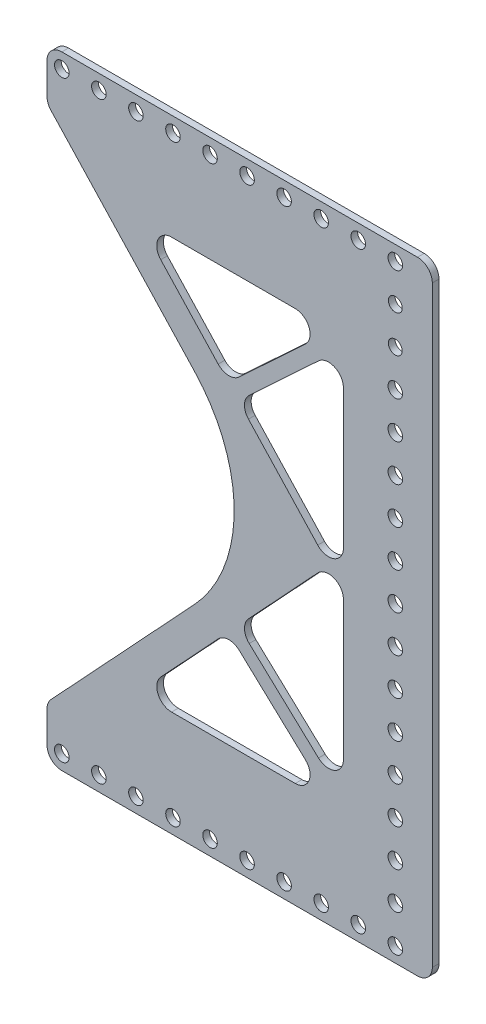
SolidWorks part; units mm, degrees
ref_plane "Front Plane" through (0, 0, 0) normal (0, 0, 1) x (1, 0, 0)
ref_plane "Top Plane" through (0, 0, 0) normal (0, 1, 0) x (1, 0, 0)
ref_plane "Right Plane" through (0, 0, 0) normal (1, 0, 0) x (0, 0, -1)
sketch "Sketch1" plane through (0, 0, 0) normal (0, 0, 1) x (1, 0, 0)
  line L0 (238.8067, 781.2872) -> (222.2967, 781.2872)
  line L4 (176.5767, 781.2872) -> (116.8867, 781.2872)
  line L5 (113.1687, 754.4243) -> (162.3479, 701.6037)
  line L6 (243.8867, 776.2072) -> (243.8867, 666.9872)
  line L7 (111.8067, 757.8859) -> (111.8067, 776.2072)
  line L8 (150.787, 728.9305) -> (170.4738, 707.786)
  line L9 (213.4067, 674.5852) -> (213.4067, 722.2064)
  line L10 (196.902, 737.4722) -> (154.5049, 737.4722)
  line L11 (243.8867, 557.7672) -> (243.8867, 666.9872)
  line L12 (238.8067, 552.6872) -> (222.2967, 552.6872)
  line L16 (113.1687, 579.55) -> (162.3479, 632.3706)
  line L17 (176.5767, 552.6872) -> (116.8867, 552.6872)
  line L18 (111.8067, 576.0884) -> (111.8067, 557.7672)
  line L19 (200.3636, 728.6742) -> (177.6534, 707.5296)
  line L20 (180.8588, 637.3423) -> (204.6087, 662.8508)
  line L21 (204.8651, 725.9243) -> (181.1151, 703.8117)
  line L22 (180.8588, 696.632) -> (204.6087, 671.1235)
  line L23 (213.4067, 659.3892) -> (213.4067, 611.768)
  line L24 (204.8651, 608.05) -> (181.1151, 630.1627)
  line L25 (200.3636, 605.3001) -> (177.6534, 626.4447)
  line L26 (150.787, 605.0438) -> (170.4738, 626.1884)
  line L27 (196.902, 596.5022) -> (154.5049, 596.5022)
  line L28 (222.2967, 552.6872) -> (176.5767, 552.6872)
  line L29 (222.2967, 781.2872) -> (176.5767, 781.2872)
  arc A0 (238.8067, 781.2872) -> (243.8867, 776.2072) centre (238.8067, 776.2072) cw
  arc A5 (116.8867, 781.2872) -> (111.8067, 776.2072) centre (116.8867, 776.2072) ccw
  circle A6 centre (142.2867, 768.5872) radius 2.4892
  circle A7 centre (154.9867, 768.5872) radius 2.4892
  circle A8 centre (167.6867, 768.5872) radius 2.4892
  circle A9 centre (231.1867, 743.1872) radius 2.3719
  circle A10 centre (231.1867, 730.4872) radius 2.4892
  circle A11 centre (231.1867, 717.7872) radius 2.4892
  circle A12 centre (231.1867, 705.0872) radius 2.4892
  circle A13 centre (231.1867, 692.3872) radius 2.4892
  arc A14 (113.1687, 754.4243) -> (111.8067, 757.8859) centre (116.8867, 757.8859) cw
  arc A15 (204.6087, 671.1235) -> (213.4067, 674.5852) centre (208.3267, 674.5852) ccw
  arc A16 (150.787, 728.9305) -> (154.5049, 737.4722) centre (154.5049, 732.3922) cw
  arc A17 (238.8067, 552.6872) -> (243.8867, 557.7672) centre (238.8067, 557.7672) ccw
  circle A22 centre (167.6867, 565.3872) radius 2.4892
  circle A23 centre (154.9867, 565.3872) radius 2.4892
  circle A24 centre (142.2867, 565.3872) radius 2.4892
  arc A25 (113.1687, 579.55) -> (111.8067, 576.0884) centre (116.8867, 576.0884) ccw
  arc A26 (116.8867, 552.6872) -> (111.8067, 557.7672) centre (116.8867, 557.7672) cw
  circle A27 centre (231.1867, 616.1872) radius 2.4892
  circle A28 centre (231.1867, 603.4872) radius 2.4892
  circle A29 centre (231.1867, 590.7872) radius 2.4892
  circle A30 centre (231.1867, 565.3872) radius 2.4892
  circle A31 centre (231.1867, 768.5872) radius 2.4892
  arc A32 (162.3479, 701.6037) -> (162.3479, 632.3706) centre (125.1681, 666.9872) cw
  circle A33 centre (231.1867, 654.2872) radius 2.4892
  circle A34 centre (231.1867, 641.5872) radius 2.4892
  circle A35 centre (231.1867, 628.8872) radius 2.4892
  circle A36 centre (116.8867, 768.5872) radius 2.4892
  circle A37 centre (129.5867, 768.5872) radius 2.4892
  circle A38 centre (129.5867, 565.3872) radius 2.4892
  circle A39 centre (116.8867, 565.3872) radius 2.4892
  arc A40 (181.1151, 703.8117) -> (180.8588, 696.632) centre (184.5767, 700.0937) ccw
  arc A41 (204.8651, 725.9243) -> (213.4067, 722.2064) centre (208.3267, 722.2064) cw
  arc A42 (200.3636, 728.6742) -> (196.902, 737.4722) centre (196.902, 732.3922) ccw
  arc A43 (177.6534, 707.5296) -> (170.4738, 707.786) centre (174.1918, 711.2476) cw
  arc A44 (204.6087, 662.8508) -> (213.4067, 659.3892) centre (208.3267, 659.3892) cw
  arc A45 (181.1151, 630.1627) -> (180.8588, 637.3423) centre (184.5767, 633.8806) cw
  arc A46 (204.8651, 608.05) -> (213.4067, 611.768) centre (208.3267, 611.768) ccw
  arc A47 (200.3636, 605.3001) -> (196.902, 596.5022) centre (196.902, 601.5822) cw
  arc A48 (177.6534, 626.4447) -> (170.4738, 626.1884) centre (174.1918, 622.7267) ccw
  arc A49 (150.787, 605.0438) -> (154.5049, 596.5022) centre (154.5049, 601.5822) ccw
  circle A50 centre (231.1867, 679.6872) radius 2.4892
  circle A51 centre (231.1867, 666.9872) radius 2.4892
  circle A52 centre (231.1867, 755.8872) radius 2.3719
  circle A53 centre (231.1867, 578.0872) radius 2.4892
  circle A54 centre (180.3867, 565.3872) radius 2.4892
  circle A55 centre (193.0867, 565.3872) radius 2.4892
  circle A56 centre (205.7867, 565.3872) radius 2.4892
  circle A57 centre (218.4867, 565.3872) radius 2.4892
  circle A58 centre (180.3867, 768.5872) radius 2.4892
  circle A59 centre (193.0867, 768.5872) radius 2.4892
  circle A60 centre (205.7867, 768.5872) radius 2.4892
  circle A61 centre (218.4867, 768.5872) radius 2.4892
  point P14 (243.8867, 666.9872)
  point P17 (218.4867, 666.9872)
  dimension "D1" = 5
  dimension "D2" = 5
extrude "Boss-Extrude1" add sketch "Sketch1" along normal blind 2.286
sketch "Sketch2" [suppressed] plane through (0, 0, 2.286) normal (0, 0, 1) x (1, 0, 0)
  line L1 (243.8867, 666.9872) -> (166.9629, 666.9872) construction
  line L2 (243.8867, 557.7672) -> (243.8867, 776.2072) construction
  circle A0 centre (164.6497, 729.7313) radius 2.54
  circle A1 centre (181.8544, 724.0904) radius 2.54
  circle A2 centre (198.8305, 691.9777) radius 2.54
  circle A3 centre (204.3595, 709.5031) radius 2.54
  circle A5 centre (198.8305, 641.9966) radius 2.54
  circle A6 centre (204.3595, 624.4712) radius 2.54
  circle A7 centre (181.8544, 609.8839) radius 2.54
  circle A8 centre (164.6497, 604.243) radius 2.54
  dimension "D1" = 5.08
sketch "Sketch3" plane through (0, 0, 2.286) normal (0, 0, 1) x (1, 0, 0)
  line L0 (111.8067, 773.6672) -> (243.8867, 773.6672)
  line L1 (111.8067, 776.2072) -> (111.8067, 757.8859) construction
  line L2 (243.8867, 557.7672) -> (243.8867, 776.2072) construction
  line L3 (111.8067, 560.3072) -> (243.8867, 560.3072)
  line L4 (238.8067, 781.2872) -> (116.8867, 781.2872) construction
  line L5 (116.8867, 552.6872) -> (238.8067, 552.6872) construction
  line L6 (111.8067, 576.0884) -> (111.8067, 557.7672) construction
  line L7 (116.8867, 552.6872) -> (238.8067, 552.6872)
  line L8 (111.8067, 576.0884) -> (111.8067, 557.7672)
  line L9 (243.8867, 557.7672) -> (243.8867, 776.2072)
  line L10 (238.8067, 781.2872) -> (116.8867, 781.2872)
  line L11 (111.8067, 776.2072) -> (111.8067, 757.8859)
  arc A1 (116.8867, 781.2872) -> (111.8067, 776.2072) centre (116.8867, 776.2072) ccw construction
  arc A2 (243.8867, 776.2072) -> (238.8067, 781.2872) centre (238.8067, 776.2072) ccw construction
  arc A3 (238.8067, 552.6872) -> (243.8867, 557.7672) centre (238.8067, 557.7672) ccw construction
  arc A4 (111.8067, 557.7672) -> (116.8867, 552.6872) centre (116.8867, 557.7672) ccw construction
  arc A5 (238.8067, 552.6872) -> (243.8867, 557.7672) centre (238.8067, 557.7672) ccw
  arc A6 (111.8067, 557.7672) -> (116.8867, 552.6872) centre (116.8867, 557.7672) ccw
  arc A7 (243.8867, 776.2072) -> (238.8067, 781.2872) centre (238.8067, 776.2072) ccw
  arc A8 (116.8867, 781.2872) -> (111.8067, 776.2072) centre (116.8867, 776.2072) ccw
  point P4 (0, 0)
  point P11 (0, 0)
  point P12 (237.4757, 557.7672)
  point P15 (0, 0)
  point P16 (0, 0)
  dimension "D1" = 7.62
  dimension "D2" = 7.62
extrude "Cut-Extrude1" cut sketch "Sketch3" against normal through all contours L8 A6 L7 A5 L9 L3 | L10 A8 L11 L0 L9 A7
fillet "Fillet1" radius 5.08 4 edges at (243.8867, 560.3072, 1.143) (111.8067, 560.3072, 1.143) (243.8867, 773.6672, 1.143) (111.8067, 773.6672, 1.143)
